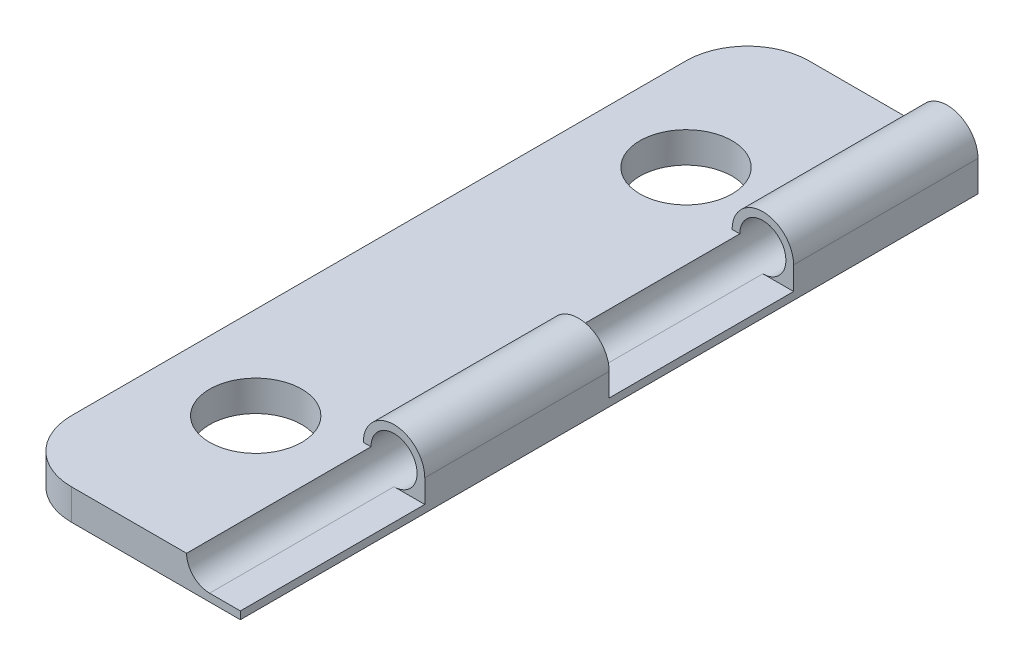
SolidWorks part; units mm, degrees
ref_plane "Alzado" through (0, 0, 0) normal (0, 0, 1) x (1, 0, 0)
ref_plane "Planta" through (0, 0, 0) normal (0, 1, 0) x (1, 0, 0)
ref_plane "Vista lateral" through (0, 0, 0) normal (1, 0, 0) x (0, 0, -1)
sketch "Croquis1" plane through (0, 0, 0) normal (0, 1, 0) x (1, 0, 0)
  line L1 (0, 0) -> (7.5, 0)
  line L2 (0, 0) -> (0, 24)
  line L3 (0, 24) -> (7.5, 24)
  line L4 (7.5, 0) -> (7.5, 24)
  dimension "D1" = 7.5
  dimension "D2" = 24
extrude "Saliente-Extruir1" add sketch "Croquis1" along normal blind 1
sketch "Croquis2" plane through (0, 0, -24) normal (0, 0, -1) x (-1, 0, 0)
  line L1 (-7.5, 0) -> (0, 0) construction
  line L2 (-7.5, 1) -> (-7.5, 0) construction
  circle A0 centre (-6.5, 1) radius 1
  dimension "D1" = 2
extrude "Saliente-Extruir2" add sketch "Croquis2" against normal blind 6
ref_plane "Plano1" through (0, 0, -12) normal (0, 0, 1) x (1, 0, 0)
sketch "Croquis3" plane through (0, 0, -12) normal (0, 0, 1) x (1, 0, 0)
  line L0 (5.5, 1) -> (7.5, 1) construction
  circle A0 centre (6.5, 1) radius 1
extrude "Saliente-Extruir3" add sketch "Croquis3" along normal blind 6
sketch "Croquis4" plane through (0, 0, -24) normal (0, 0, -1) x (-1, 0, 0)
  circle A0 centre (-6.5, 1) radius 0.75
extrude "Cortar-Extruir1" cut sketch "Croquis4" against normal blind 24
fillet "Redondeo1" radius 2 2 edges at (0, 0.5, 0) (0, 0.5, -24)
sketch "Croquis5" plane through (0, 1, 0) normal (0, 1, 0) x (1, 0, 0)
  line L0 (0, 22) -> (0, 2) construction
  line L1 (5.5, 24) -> (2, 24) construction
  line L2 (2, 0) -> (5.75, 0) construction
  circle A0 centre (3, 19) radius 1.5
  circle A1 centre (3, 5) radius 1.5
  dimension "D1" = 3
  dimension "D2" = 3
  dimension "D4" = 5
  dimension "D3" = 5
extrude "Cortar-Extruir2" cut sketch "Croquis5" against normal blind 18
sketch "Croquis6" plane through (0, 0, 0) normal (0, 0, 1) x (1, 0, 0)
  line L0 (6.5, 0.25) -> (7.5, 0.25)
  line L1 (7.5, 1) -> (7.5, 0) construction
  line L2 (7.5, 0.25) -> (7.5, 1)
  line L3 (7.5, 1) -> (7.25, 1)
  line L4 (7.25, 1) -> (6.5, 0.25)
  arc A0 (5.75, 1) -> (7.25, 1) centre (6.5, 1) ccw construction
extrude "Cortar-Extruir3" cut sketch "Croquis6" against normal blind 6
sketch "Croquis7" plane through (0, 0, -12) normal (0, 0, -1) x (-1, 0, 0)
  line L5 (-6.5, 0.25) -> (-7.5, 0.25)
  line L6 (-7.5, 0.25) -> (-7.5, 1)
  line L8 (-7.5, 1) -> (-6.8002, 1)
  line L9 (-6.8002, 1) -> (-6.5, 0.25)
extrude "Cortar-Extruir4" cut sketch "Croquis7" along normal blind 6
